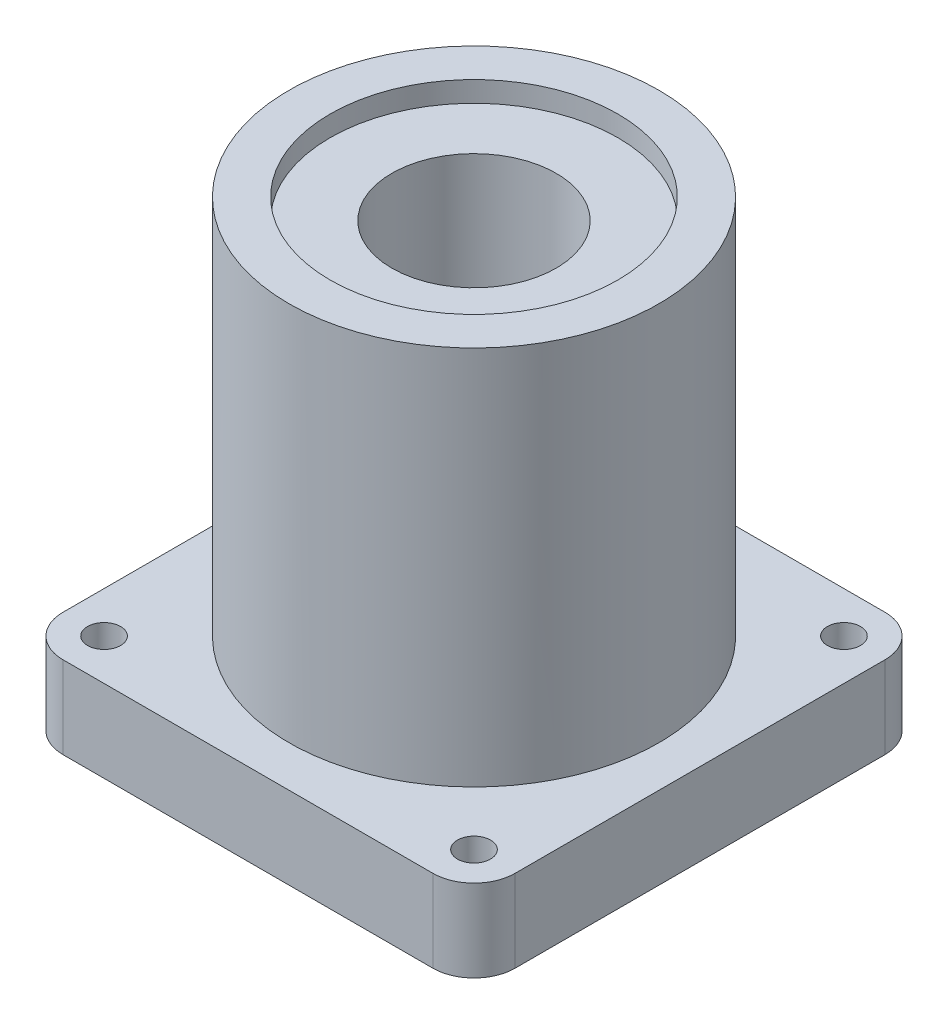
SolidWorks part; units mm, degrees
material "PW50:30:C1:0:1:2:Re:10:"
ref_plane "front" through (0, 0, 0) normal (0, 0, 1) x (1, 0, 0)
ref_plane "top" through (0, 0, 0) normal (0, 1, 0) x (1, 0, 0)
ref_plane "side" through (0, 0, 0) normal (1, 0, 0) x (0, 0, -1)
sketch "Sketch1" plane through (0, 0, 0) normal (0, 1, 0) x (1, 0, 0)
  line L0 (-34.925, -34.925) -> (34.925, -34.925)
  line L1 (-34.925, -34.925) -> (-34.925, 34.925)
  line L2 (34.925, 34.925) -> (-34.925, 34.925)
  line L3 (34.925, 34.925) -> (34.925, -34.925)
  line L4 (34.925, 0) -> (0, 0) construction
  line L5 (0, -34.925) -> (0, 0) construction
  dimension "D1" = 69.85
extrude "Base-Extrude" add sketch "Sketch1" along normal blind 12.7
sketch "Sketch2" plane through (0, 0, 0) normal (0, 1, 0) x (-1, 0, 0)
  circle A0 centre (0, 0) radius 28.575
  dimension "D1" = 57.15
extrude "Boss-Extrude1" add sketch "Sketch2" along normal blind 71.4375
sketch "Sketch3" plane through (0, 71.4375, 0) normal (0, 1, 0) x (-1, 0, 0)
  circle A0 centre (0, 0) radius 12.7
  dimension "D1" = 25.4
extrude "Cut-Extrude1" cut sketch "Sketch3" against normal through all
sketch "Sketch4" plane through (0, 71.4375, 0) normal (0, 1, 0) x (-1, 0, 0)
  circle A0 centre (0, 0) radius 22.225
  dimension "D1" = 44.45
extrude "Cut-Extrude2" cut sketch "Sketch4" against normal blind 3.175
fillet "Fillet1" radius 6.35 4 edges at (-34.925, 6.35, 34.925) (34.925, 6.35, 34.925) (34.925, 6.35, -34.925) (-34.925, 6.35, -34.925)
hole_wizard "1/4-20 Tapped Hole2" positions "Sketch8" profile "Sketch7" tap size "1/4-20" standard "Ansi Inch"
sketch "Sketch8" plane through (0, 12.7, 0) normal (0, 1, 0) x (-1, 0, 0)
  arc A0 (28.575, -34.925) -> (34.925, -28.575) centre (28.575, -28.575) ccw construction
  point P0 (28.575, -28.575)
sketch "Sketch7" plane through (-28.575, 12.7, -28.575) normal (1, 0, 0) x (0, 0, 1)
  line L0 (0, 0) -> (0, 20.5838)
  line L1 (0, 20.5838) -> (2.5527, 19.05)
  line L2 (2.5527, 19.05) -> (2.5527, 0)
  line L5 (2.5527, 0) -> (0, 0)
  line L10 (0, 20.5838) -> (-2.5527, 19.05) construction
  line L11 (0, -6.35) -> (0, 107.95) construction
  dimension "Hole Dia." = 5.1054
  dimension "Hole Depth" = 19.05
  dimension "Drill Angle" = 118
cosmetic thread "Cosmetic Thread2" parameters "D1"=12.7, "D2"=6.35
pattern_circular "CirPattern2" count 4 over 360 about axis through (0, 0, 0) along (0, 1, 0) of "1/4-20 Tapped Hole2"
